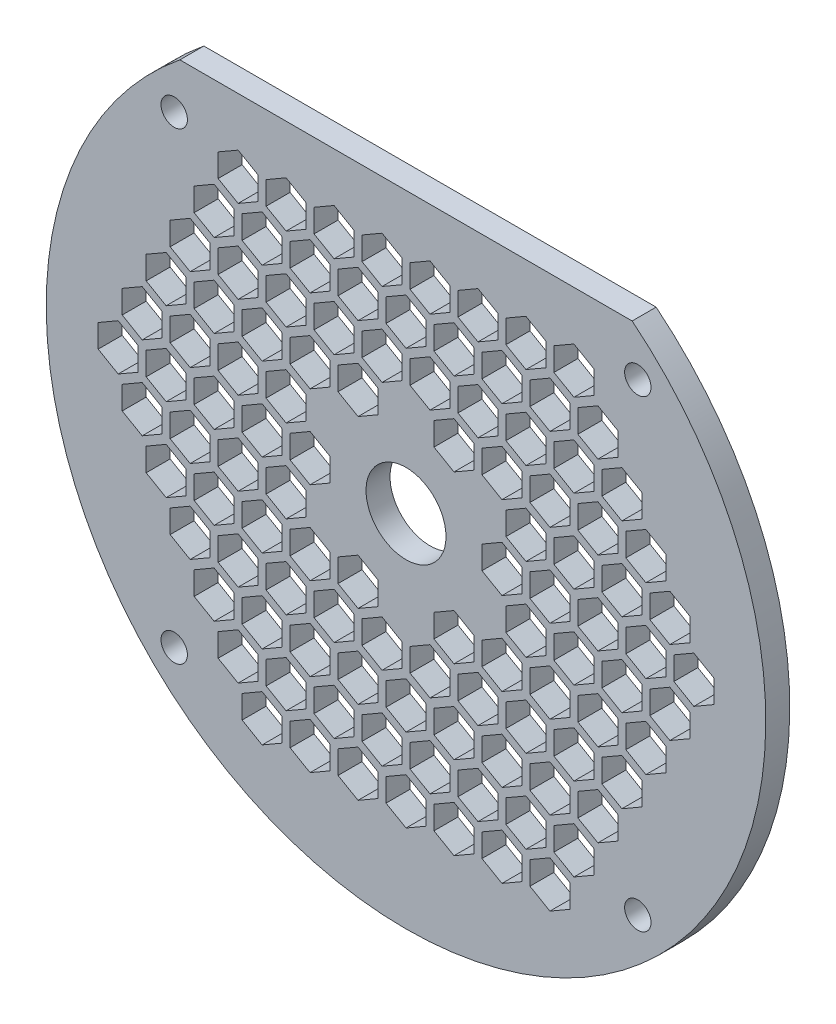
SolidWorks part; units mm, degrees
ref_plane "前视基准面" through (0, 0, 0) normal (0, 0, 1) x (1, 0, 0)
ref_plane "上视基准面" through (0, 0, 0) normal (0, 1, 0) x (1, 0, 0)
ref_plane "右视基准面" through (0, 0, 0) normal (1, 0, 0) x (0, 0, -1)
sketch "草图1" plane through (0, 0, 0) normal (0, 0, 1) x (1, 0, 0)
  circle A0 centre (0, 0) radius 90
extrude "凸台-拉伸1" add sketch "草图1" along normal blind 6
sketch "草图3" plane through (0, 0, 0) normal (0, 0, 1) x (1, 0, 0)
  circle A0 centre (0, 0) radius 10
extrude "切除-拉伸2" cut sketch "草图3" along normal through all
sketch "草图4" plane through (0, 0, 0) normal (0, 0, 1) x (1, 0, 0)
  circle A0 centre (57.9828, 57.9828) radius 3.3
  circle A1 centre (-57.9828, 57.9828) radius 3.3
  circle A2 centre (-57.9828, -57.9828) radius 3.3
  circle A3 centre (57.9828, -57.9828) radius 3.3
extrude "切除-拉伸3" cut sketch "草图4" along normal through all
sketch "草图5" plane through (0, 0, 0) normal (0, 0, 1) x (1, 0, 0)
  line L0 (-110, 70) -> (110, 70)
  line L1 (110, 70) -> (110, 110)
  line L2 (110, 110) -> (-110, 110)
  line L3 (-110, 110) -> (-110, 70)
extrude "切除-拉伸4" cut sketch "草图5" along normal through all
sketch "草图6" plane through (0, 0, 0) normal (0, 0, 1) x (1, 0, 0)
  line L0 (0, -56.5785) -> (5, -59.4653)
  line L1 (5, -59.4653) -> (5, -65.2388)
  line L2 (5, -65.2388) -> (0, -68.1255)
  line L3 (0, -68.1255) -> (-5, -65.2388)
  line L4 (-5, -65.2388) -> (-5, -59.4653)
  line L5 (-5, -59.4653) -> (0, -56.5785)
  line L6 (12, -56.5785) -> (17, -59.4653)
  line L7 (17, -59.4653) -> (17, -65.2388)
  line L8 (17, -65.2388) -> (12, -68.1255)
  line L9 (12, -68.1255) -> (7, -65.2388)
  line L10 (7, -65.2388) -> (7, -59.4653)
  line L11 (7, -59.4653) -> (12, -56.5785)
  line L12 (-12, -56.5785) -> (-7, -59.4653)
  line L13 (-7, -59.4653) -> (-7, -65.2388)
  line L14 (-7, -65.2388) -> (-12, -68.1255)
  line L15 (-12, -68.1255) -> (-17, -65.2388)
  line L16 (-17, -65.2388) -> (-17, -59.4653)
  line L17 (-17, -59.4653) -> (-12, -56.5785)
  line L18 (24, -56.5785) -> (29, -59.4653)
  line L19 (29, -59.4653) -> (29, -65.2388)
  line L20 (29, -65.2388) -> (24, -68.1255)
  line L21 (24, -68.1255) -> (19, -65.2388)
  line L22 (19, -65.2388) -> (19, -59.4653)
  line L23 (19, -59.4653) -> (24, -56.5785)
  line L24 (-24, -56.5785) -> (-19, -59.4653)
  line L25 (-19, -59.4653) -> (-19, -65.2388)
  line L26 (-19, -65.2388) -> (-24, -68.1255)
  line L27 (-24, -68.1255) -> (-29, -65.2388)
  line L28 (-29, -65.2388) -> (-29, -59.4653)
  line L29 (-29, -59.4653) -> (-24, -56.5785)
  line L30 (36, -56.5785) -> (41, -59.4653)
  line L31 (41, -59.4653) -> (41, -65.2388)
  line L32 (41, -65.2388) -> (36, -68.1255)
  line L33 (36, -68.1255) -> (31, -65.2388)
  line L34 (31, -65.2388) -> (31, -59.4653)
  line L35 (31, -59.4653) -> (36, -56.5785)
  line L36 (-36, -56.5785) -> (-31, -59.4653)
  line L37 (-31, -59.4653) -> (-31, -65.2388)
  line L38 (-31, -65.2388) -> (-36, -68.1255)
  line L39 (-36, -68.1255) -> (-41, -65.2388)
  line L40 (-41, -65.2388) -> (-41, -59.4653)
  line L41 (-41, -59.4653) -> (-36, -56.5785)
  line L42 (6, -46.1865) -> (11, -49.0733)
  line L43 (11, -49.0733) -> (11, -54.8468)
  line L44 (11, -54.8468) -> (6, -57.7335)
  line L45 (6, -57.7335) -> (1, -54.8468)
  line L46 (1, -54.8468) -> (1, -49.0733)
  line L47 (1, -49.0733) -> (6, -46.1865)
  line L48 (-6, -46.1865) -> (-1, -49.0733)
  line L49 (-1, -49.0733) -> (-1, -54.8468)
  line L50 (-1, -54.8468) -> (-6, -57.7335)
  line L51 (-6, -57.7335) -> (-11, -54.8468)
  line L52 (-11, -54.8468) -> (-11, -49.0733)
  line L53 (-11, -49.0733) -> (-6, -46.1865)
  line L54 (18, -46.1865) -> (23, -49.0733)
  line L55 (23, -49.0733) -> (23, -54.8468)
  line L56 (23, -54.8468) -> (18, -57.7335)
  line L57 (18, -57.7335) -> (13, -54.8468)
  line L58 (13, -54.8468) -> (13, -49.0733)
  line L59 (13, -49.0733) -> (18, -46.1865)
  line L60 (-18, -46.1865) -> (-13, -49.0733)
  line L61 (-13, -49.0733) -> (-13, -54.8468)
  line L62 (-13, -54.8468) -> (-18, -57.7335)
  line L63 (-18, -57.7335) -> (-23, -54.8468)
  line L64 (-23, -54.8468) -> (-23, -49.0733)
  line L65 (-23, -49.0733) -> (-18, -46.1865)
  line L66 (30, -46.1865) -> (35, -49.0733)
  line L67 (35, -49.0733) -> (35, -54.8468)
  line L68 (35, -54.8468) -> (30, -57.7335)
  line L69 (30, -57.7335) -> (25, -54.8468)
  line L70 (25, -54.8468) -> (25, -49.0733)
  line L71 (25, -49.0733) -> (30, -46.1865)
  line L72 (-30, -46.1865) -> (-25, -49.0733)
  line L73 (-25, -49.0733) -> (-25, -54.8468)
  line L74 (-25, -54.8468) -> (-30, -57.7335)
  line L75 (-30, -57.7335) -> (-35, -54.8468)
  line L76 (-35, -54.8468) -> (-35, -49.0733)
  line L77 (-35, -49.0733) -> (-30, -46.1865)
  line L78 (42, -46.1865) -> (47, -49.0733)
  line L79 (47, -49.0733) -> (47, -54.8468)
  line L80 (47, -54.8468) -> (42, -57.7335)
  line L81 (42, -57.7335) -> (37, -54.8468)
  line L82 (37, -54.8468) -> (37, -49.0733)
  line L83 (37, -49.0733) -> (42, -46.1865)
  line L84 (-42, -46.1865) -> (-37, -49.0733)
  line L85 (-37, -49.0733) -> (-37, -54.8468)
  line L86 (-37, -54.8468) -> (-42, -57.7335)
  line L87 (-42, -57.7335) -> (-47, -54.8468)
  line L88 (-47, -54.8468) -> (-47, -49.0733)
  line L89 (-47, -49.0733) -> (-42, -46.1865)
  line L90 (0, -35.7945) -> (5, -38.6813)
  line L91 (5, -38.6813) -> (5, -44.4548)
  line L92 (5, -44.4548) -> (0, -47.3415)
  line L93 (0, -47.3415) -> (-5, -44.4548)
  line L94 (-5, -44.4548) -> (-5, -38.6813)
  line L95 (-5, -38.6813) -> (0, -35.7945)
  line L96 (12, -35.7945) -> (17, -38.6813)
  line L97 (17, -38.6813) -> (17, -44.4548)
  line L98 (17, -44.4548) -> (12, -47.3415)
  line L99 (12, -47.3415) -> (7, -44.4548)
  line L100 (7, -44.4548) -> (7, -38.6813)
  line L101 (7, -38.6813) -> (12, -35.7945)
  line L102 (-12, -35.7945) -> (-7, -38.6813)
  line L103 (-7, -38.6813) -> (-7, -44.4548)
  line L104 (-7, -44.4548) -> (-12, -47.3415)
  line L105 (-12, -47.3415) -> (-17, -44.4548)
  line L106 (-17, -44.4548) -> (-17, -38.6813)
  line L107 (-17, -38.6813) -> (-12, -35.7945)
  line L108 (24, -35.7945) -> (29, -38.6813)
  line L109 (29, -38.6813) -> (29, -44.4548)
  line L110 (29, -44.4548) -> (24, -47.3415)
  line L111 (24, -47.3415) -> (19, -44.4548)
  line L112 (19, -44.4548) -> (19, -38.6813)
  line L113 (19, -38.6813) -> (24, -35.7945)
  line L114 (-24, -35.7945) -> (-19, -38.6813)
  line L115 (-19, -38.6813) -> (-19, -44.4548)
  line L116 (-19, -44.4548) -> (-24, -47.3415)
  line L117 (-24, -47.3415) -> (-29, -44.4548)
  line L118 (-29, -44.4548) -> (-29, -38.6813)
  line L119 (-29, -38.6813) -> (-24, -35.7945)
  line L120 (36, -35.7945) -> (41, -38.6813)
  line L121 (41, -38.6813) -> (41, -44.4548)
  line L122 (41, -44.4548) -> (36, -47.3415)
  line L123 (36, -47.3415) -> (31, -44.4548)
  line L124 (31, -44.4548) -> (31, -38.6813)
  line L125 (31, -38.6813) -> (36, -35.7945)
  line L126 (-36, -35.7945) -> (-31, -38.6813)
  line L127 (-31, -38.6813) -> (-31, -44.4548)
  line L128 (-31, -44.4548) -> (-36, -47.3415)
  line L129 (-36, -47.3415) -> (-41, -44.4548)
  line L130 (-41, -44.4548) -> (-41, -38.6813)
  line L131 (-41, -38.6813) -> (-36, -35.7945)
  line L132 (48, -35.7945) -> (53, -38.6813)
  line L133 (53, -38.6813) -> (53, -44.4548)
  line L134 (53, -44.4548) -> (48, -47.3415)
  line L135 (48, -47.3415) -> (43, -44.4548)
  line L136 (43, -44.4548) -> (43, -38.6813)
  line L137 (43, -38.6813) -> (48, -35.7945)
  line L138 (-48, -35.7945) -> (-43, -38.6813)
  line L139 (-43, -38.6813) -> (-43, -44.4548)
  line L140 (-43, -44.4548) -> (-48, -47.3415)
  line L141 (-48, -47.3415) -> (-53, -44.4548)
  line L142 (-53, -44.4548) -> (-53, -38.6813)
  line L143 (-53, -38.6813) -> (-48, -35.7945)
extrude "切除-拉伸5" cut sketch "草图6" along normal through all
sketch "草图8" plane through (0, 0, 0) normal (0, 0, 1) x (1, 0, 0)
  line L0 (6, -25.4025) -> (11, -28.2893)
  line L1 (11, -28.2893) -> (11, -34.0628)
  line L2 (11, -34.0628) -> (6, -36.9495)
  line L3 (6, -36.9495) -> (1, -34.0628)
  line L4 (1, -34.0628) -> (1, -28.2893)
  line L5 (1, -28.2893) -> (6, -25.4025)
  line L6 (-6, -25.4025) -> (-1, -28.2893)
  line L7 (-1, -28.2893) -> (-1, -34.0628)
  line L8 (-1, -34.0628) -> (-6, -36.9495)
  line L9 (-6, -36.9495) -> (-11, -34.0628)
  line L10 (-11, -34.0628) -> (-11, -28.2893)
  line L11 (-11, -28.2893) -> (-6, -25.4025)
  line L12 (18, -25.4025) -> (23, -28.2893)
  line L13 (23, -28.2893) -> (23, -34.0628)
  line L14 (23, -34.0628) -> (18, -36.9495)
  line L15 (18, -36.9495) -> (13, -34.0628)
  line L16 (13, -34.0628) -> (13, -28.2893)
  line L17 (13, -28.2893) -> (18, -25.4025)
  line L18 (-18, -25.4025) -> (-13, -28.2893)
  line L19 (-13, -28.2893) -> (-13, -34.0628)
  line L20 (-13, -34.0628) -> (-18, -36.9495)
  line L21 (-18, -36.9495) -> (-23, -34.0628)
  line L22 (-23, -34.0628) -> (-23, -28.2893)
  line L23 (-23, -28.2893) -> (-18, -25.4025)
  line L24 (30, -25.4025) -> (35, -28.2893)
  line L25 (35, -28.2893) -> (35, -34.0628)
  line L26 (35, -34.0628) -> (30, -36.9495)
  line L27 (30, -36.9495) -> (25, -34.0628)
  line L28 (25, -34.0628) -> (25, -28.2893)
  line L29 (25, -28.2893) -> (30, -25.4025)
  line L30 (-30, -25.4025) -> (-25, -28.2893)
  line L31 (-25, -28.2893) -> (-25, -34.0628)
  line L32 (-25, -34.0628) -> (-30, -36.9495)
  line L33 (-30, -36.9495) -> (-35, -34.0628)
  line L34 (-35, -34.0628) -> (-35, -28.2893)
  line L35 (-35, -28.2893) -> (-30, -25.4025)
  line L36 (42, -25.4025) -> (47, -28.2893)
  line L37 (47, -28.2893) -> (47, -34.0628)
  line L38 (47, -34.0628) -> (42, -36.9495)
  line L39 (42, -36.9495) -> (37, -34.0628)
  line L40 (37, -34.0628) -> (37, -28.2893)
  line L41 (37, -28.2893) -> (42, -25.4025)
  line L42 (-42, -25.4025) -> (-37, -28.2893)
  line L43 (-37, -28.2893) -> (-37, -34.0628)
  line L44 (-37, -34.0628) -> (-42, -36.9495)
  line L45 (-42, -36.9495) -> (-47, -34.0628)
  line L46 (-47, -34.0628) -> (-47, -28.2893)
  line L47 (-47, -28.2893) -> (-42, -25.4025)
  line L48 (54, -25.4025) -> (59, -28.2893)
  line L49 (59, -28.2893) -> (59, -34.0628)
  line L50 (59, -34.0628) -> (54, -36.9495)
  line L51 (54, -36.9495) -> (49, -34.0628)
  line L52 (49, -34.0628) -> (49, -28.2893)
  line L53 (49, -28.2893) -> (54, -25.4025)
  line L54 (-54, -25.4025) -> (-49, -28.2893)
  line L55 (-49, -28.2893) -> (-49, -34.0628)
  line L56 (-49, -34.0628) -> (-54, -36.9495)
  line L57 (-54, -36.9495) -> (-59, -34.0628)
  line L58 (-59, -34.0628) -> (-59, -28.2893)
  line L59 (-59, -28.2893) -> (-54, -25.4025)
  line L60 (12, -15.0105) -> (17, -17.8973)
  line L61 (17, -17.8973) -> (17, -23.6708)
  line L62 (17, -23.6708) -> (12, -26.5575)
  line L63 (12, -26.5575) -> (7, -23.6708)
  line L64 (7, -23.6708) -> (7, -17.8973)
  line L65 (7, -17.8973) -> (12, -15.0105)
  line L66 (-12, -15.0105) -> (-7, -17.8973)
  line L67 (-7, -17.8973) -> (-7, -23.6708)
  line L68 (-7, -23.6708) -> (-12, -26.5575)
  line L69 (-12, -26.5575) -> (-17, -23.6708)
  line L70 (-17, -23.6708) -> (-17, -17.8973)
  line L71 (-17, -17.8973) -> (-12, -15.0105)
  line L72 (24, -15.0105) -> (29, -17.8973)
  line L73 (29, -17.8973) -> (29, -23.6708)
  line L74 (29, -23.6708) -> (24, -26.5575)
  line L75 (24, -26.5575) -> (19, -23.6708)
  line L76 (19, -23.6708) -> (19, -17.8973)
  line L77 (19, -17.8973) -> (24, -15.0105)
  line L78 (-24, -15.0105) -> (-19, -17.8973)
  line L79 (-19, -17.8973) -> (-19, -23.6708)
  line L80 (-19, -23.6708) -> (-24, -26.5575)
  line L81 (-24, -26.5575) -> (-29, -23.6708)
  line L82 (-29, -23.6708) -> (-29, -17.8973)
  line L83 (-29, -17.8973) -> (-24, -15.0105)
  line L84 (36, -15.0105) -> (41, -17.8973)
  line L85 (41, -17.8973) -> (41, -23.6708)
  line L86 (41, -23.6708) -> (36, -26.5575)
  line L87 (36, -26.5575) -> (31, -23.6708)
  line L88 (31, -23.6708) -> (31, -17.8973)
  line L89 (31, -17.8973) -> (36, -15.0105)
  line L90 (-36, -15.0105) -> (-31, -17.8973)
  line L91 (-31, -17.8973) -> (-31, -23.6708)
  line L92 (-31, -23.6708) -> (-36, -26.5575)
  line L93 (-36, -26.5575) -> (-41, -23.6708)
  line L94 (-41, -23.6708) -> (-41, -17.8973)
  line L95 (-41, -17.8973) -> (-36, -15.0105)
  line L96 (48, -15.0105) -> (53, -17.8973)
  line L97 (53, -17.8973) -> (53, -23.6708)
  line L98 (53, -23.6708) -> (48, -26.5575)
  line L99 (48, -26.5575) -> (43, -23.6708)
  line L100 (43, -23.6708) -> (43, -17.8973)
  line L101 (43, -17.8973) -> (48, -15.0105)
  line L102 (-48, -15.0105) -> (-43, -17.8973)
  line L103 (-43, -17.8973) -> (-43, -23.6708)
  line L104 (-43, -23.6708) -> (-48, -26.5575)
  line L105 (-48, -26.5575) -> (-53, -23.6708)
  line L106 (-53, -23.6708) -> (-53, -17.8973)
  line L107 (-53, -17.8973) -> (-48, -15.0105)
  line L108 (60, -15.0105) -> (65, -17.8973)
  line L109 (65, -17.8973) -> (65, -23.6708)
  line L110 (65, -23.6708) -> (60, -26.5575)
  line L111 (60, -26.5575) -> (55, -23.6708)
  line L112 (55, -23.6708) -> (55, -17.8973)
  line L113 (55, -17.8973) -> (60, -15.0105)
  line L114 (-60, -15.0105) -> (-55, -17.8973)
  line L115 (-55, -17.8973) -> (-55, -23.6708)
  line L116 (-55, -23.6708) -> (-60, -26.5575)
  line L117 (-60, -26.5575) -> (-65, -23.6708)
  line L118 (-65, -23.6708) -> (-65, -17.8973)
  line L119 (-65, -17.8973) -> (-60, -15.0105)
  line L120 (30, -4.6185) -> (35, -7.5053)
  line L121 (35, -7.5053) -> (35, -13.2788)
  line L122 (35, -13.2788) -> (30, -16.1655)
  line L123 (30, -16.1655) -> (25, -13.2788)
  line L124 (25, -13.2788) -> (25, -7.5053)
  line L125 (25, -7.5053) -> (30, -4.6185)
  line L126 (-30, -4.6185) -> (-25, -7.5053)
  line L127 (-25, -7.5053) -> (-25, -13.2788)
  line L128 (-25, -13.2788) -> (-30, -16.1655)
  line L129 (-30, -16.1655) -> (-35, -13.2788)
  line L130 (-35, -13.2788) -> (-35, -7.5053)
  line L131 (-35, -7.5053) -> (-30, -4.6185)
  line L132 (42, -4.6185) -> (47, -7.5053)
  line L133 (47, -7.5053) -> (47, -13.2788)
  line L134 (47, -13.2788) -> (42, -16.1655)
  line L135 (42, -16.1655) -> (37, -13.2788)
  line L136 (37, -13.2788) -> (37, -7.5053)
  line L137 (37, -7.5053) -> (42, -4.6185)
  line L138 (-42, -4.6185) -> (-37, -7.5053)
  line L139 (-37, -7.5053) -> (-37, -13.2788)
  line L140 (-37, -13.2788) -> (-42, -16.1655)
  line L141 (-42, -16.1655) -> (-47, -13.2788)
  line L142 (-47, -13.2788) -> (-47, -7.5053)
  line L143 (-47, -7.5053) -> (-42, -4.6185)
  line L144 (54, -4.6185) -> (59, -7.5053)
  line L145 (59, -7.5053) -> (59, -13.2788)
  line L146 (59, -13.2788) -> (54, -16.1655)
  line L147 (54, -16.1655) -> (49, -13.2788)
  line L148 (49, -13.2788) -> (49, -7.5053)
  line L149 (49, -7.5053) -> (54, -4.6185)
  line L150 (-54, -4.6185) -> (-49, -7.5053)
  line L151 (-49, -7.5053) -> (-49, -13.2788)
  line L152 (-49, -13.2788) -> (-54, -16.1655)
  line L153 (-54, -16.1655) -> (-59, -13.2788)
  line L154 (-59, -13.2788) -> (-59, -7.5053)
  line L155 (-59, -7.5053) -> (-54, -4.6185)
  line L156 (66, -4.6185) -> (71, -7.5053)
  line L157 (71, -7.5053) -> (71, -13.2788)
  line L158 (71, -13.2788) -> (66, -16.1655)
  line L159 (66, -16.1655) -> (61, -13.2788)
  line L160 (61, -13.2788) -> (61, -7.5053)
  line L161 (61, -7.5053) -> (66, -4.6185)
  line L162 (-66, -4.6185) -> (-61, -7.5053)
  line L163 (-61, -7.5053) -> (-61, -13.2788)
  line L164 (-61, -13.2788) -> (-66, -16.1655)
  line L165 (-66, -16.1655) -> (-71, -13.2788)
  line L166 (-71, -13.2788) -> (-71, -7.5053)
  line L167 (-71, -7.5053) -> (-66, -4.6185)
extrude "切除-拉伸7" cut sketch "草图8" along normal through all
sketch "草图9" plane through (0, 0, 0) normal (0, 0, 1) x (1, 0, 0)
  line L0 (24, 5.7735) -> (29, 2.8868)
  line L1 (29, 2.8868) -> (29, -2.8868)
  line L2 (29, -2.8868) -> (24, -5.7735)
  line L3 (24, -5.7735) -> (19, -2.8868)
  line L4 (19, -2.8868) -> (19, 2.8868)
  line L5 (19, 2.8868) -> (24, 5.7735)
  line L6 (-24, 5.7735) -> (-19, 2.8868)
  line L7 (-19, 2.8868) -> (-19, -2.8868)
  line L8 (-19, -2.8868) -> (-24, -5.7735)
  line L9 (-24, -5.7735) -> (-29, -2.8868)
  line L10 (-29, -2.8868) -> (-29, 2.8868)
  line L11 (-29, 2.8868) -> (-24, 5.7735)
  line L12 (36, 5.7735) -> (41, 2.8868)
  line L13 (41, 2.8868) -> (41, -2.8868)
  line L14 (41, -2.8868) -> (36, -5.7735)
  line L15 (36, -5.7735) -> (31, -2.8868)
  line L16 (31, -2.8868) -> (31, 2.8868)
  line L17 (31, 2.8868) -> (36, 5.7735)
  line L18 (-36, 5.7735) -> (-31, 2.8868)
  line L19 (-31, 2.8868) -> (-31, -2.8868)
  line L20 (-31, -2.8868) -> (-36, -5.7735)
  line L21 (-36, -5.7735) -> (-41, -2.8868)
  line L22 (-41, -2.8868) -> (-41, 2.8868)
  line L23 (-41, 2.8868) -> (-36, 5.7735)
  line L24 (48, 5.7735) -> (53, 2.8868)
  line L25 (53, 2.8868) -> (53, -2.8868)
  line L26 (53, -2.8868) -> (48, -5.7735)
  line L27 (48, -5.7735) -> (43, -2.8868)
  line L28 (43, -2.8868) -> (43, 2.8868)
  line L29 (43, 2.8868) -> (48, 5.7735)
  line L30 (-48, 5.7735) -> (-43, 2.8868)
  line L31 (-43, 2.8868) -> (-43, -2.8868)
  line L32 (-43, -2.8868) -> (-48, -5.7735)
  line L33 (-48, -5.7735) -> (-53, -2.8868)
  line L34 (-53, -2.8868) -> (-53, 2.8868)
  line L35 (-53, 2.8868) -> (-48, 5.7735)
  line L36 (60, 5.7735) -> (65, 2.8868)
  line L37 (65, 2.8868) -> (65, -2.8868)
  line L38 (65, -2.8868) -> (60, -5.7735)
  line L39 (60, -5.7735) -> (55, -2.8868)
  line L40 (55, -2.8868) -> (55, 2.8868)
  line L41 (55, 2.8868) -> (60, 5.7735)
  line L42 (-60, 5.7735) -> (-55, 2.8868)
  line L43 (-55, 2.8868) -> (-55, -2.8868)
  line L44 (-55, -2.8868) -> (-60, -5.7735)
  line L45 (-60, -5.7735) -> (-65, -2.8868)
  line L46 (-65, -2.8868) -> (-65, 2.8868)
  line L47 (-65, 2.8868) -> (-60, 5.7735)
  line L48 (72, 5.7735) -> (77, 2.8868)
  line L49 (77, 2.8868) -> (77, -2.8868)
  line L50 (77, -2.8868) -> (72, -5.7735)
  line L51 (72, -5.7735) -> (67, -2.8868)
  line L52 (67, -2.8868) -> (67, 2.8868)
  line L53 (67, 2.8868) -> (72, 5.7735)
  line L54 (-72, 5.7735) -> (-67, 2.8868)
  line L55 (-67, 2.8868) -> (-67, -2.8868)
  line L56 (-67, -2.8868) -> (-72, -5.7735)
  line L57 (-72, -5.7735) -> (-77, -2.8868)
  line L58 (-77, -2.8868) -> (-77, 2.8868)
  line L59 (-77, 2.8868) -> (-72, 5.7735)
  line L60 (30, 16.1655) -> (35, 13.2788)
  line L61 (35, 13.2788) -> (35, 7.5053)
  line L62 (35, 7.5053) -> (30, 4.6185)
  line L63 (30, 4.6185) -> (25, 7.5053)
  line L64 (25, 7.5053) -> (25, 13.2788)
  line L65 (25, 13.2788) -> (30, 16.1655)
  line L66 (-30, 16.1655) -> (-25, 13.2788)
  line L67 (-25, 13.2788) -> (-25, 7.5053)
  line L68 (-25, 7.5053) -> (-30, 4.6185)
  line L69 (-30, 4.6185) -> (-35, 7.5053)
  line L70 (-35, 7.5053) -> (-35, 13.2788)
  line L71 (-35, 13.2788) -> (-30, 16.1655)
  line L72 (42, 16.1655) -> (47, 13.2788)
  line L73 (47, 13.2788) -> (47, 7.5053)
  line L74 (47, 7.5053) -> (42, 4.6185)
  line L75 (42, 4.6185) -> (37, 7.5053)
  line L76 (37, 7.5053) -> (37, 13.2788)
  line L77 (37, 13.2788) -> (42, 16.1655)
  line L78 (-42, 16.1655) -> (-37, 13.2788)
  line L79 (-37, 13.2788) -> (-37, 7.5053)
  line L80 (-37, 7.5053) -> (-42, 4.6185)
  line L81 (-42, 4.6185) -> (-47, 7.5053)
  line L82 (-47, 7.5053) -> (-47, 13.2788)
  line L83 (-47, 13.2788) -> (-42, 16.1655)
  line L84 (54, 16.1655) -> (59, 13.2788)
  line L85 (59, 13.2788) -> (59, 7.5053)
  line L86 (59, 7.5053) -> (54, 4.6185)
  line L87 (54, 4.6185) -> (49, 7.5053)
  line L88 (49, 7.5053) -> (49, 13.2788)
  line L89 (49, 13.2788) -> (54, 16.1655)
  line L90 (-54, 16.1655) -> (-49, 13.2788)
  line L91 (-49, 13.2788) -> (-49, 7.5053)
  line L92 (-49, 7.5053) -> (-54, 4.6185)
  line L93 (-54, 4.6185) -> (-59, 7.5053)
  line L94 (-59, 7.5053) -> (-59, 13.2788)
  line L95 (-59, 13.2788) -> (-54, 16.1655)
  line L96 (66, 16.1655) -> (71, 13.2788)
  line L97 (71, 13.2788) -> (71, 7.5053)
  line L98 (71, 7.5053) -> (66, 4.6185)
  line L99 (66, 4.6185) -> (61, 7.5053)
  line L100 (61, 7.5053) -> (61, 13.2788)
  line L101 (61, 13.2788) -> (66, 16.1655)
  line L102 (-66, 16.1655) -> (-61, 13.2788)
  line L103 (-61, 13.2788) -> (-61, 7.5053)
  line L104 (-61, 7.5053) -> (-66, 4.6185)
  line L105 (-66, 4.6185) -> (-71, 7.5053)
  line L106 (-71, 7.5053) -> (-71, 13.2788)
  line L107 (-71, 13.2788) -> (-66, 16.1655)
  line L108 (12, 26.5575) -> (17, 23.6708)
  line L109 (17, 23.6708) -> (17, 17.8973)
  line L110 (17, 17.8973) -> (12, 15.0105)
  line L111 (12, 15.0105) -> (7, 17.8973)
  line L112 (7, 17.8973) -> (7, 23.6708)
  line L113 (7, 23.6708) -> (12, 26.5575)
  line L114 (-12, 26.5575) -> (-7, 23.6708)
  line L115 (-7, 23.6708) -> (-7, 17.8973)
  line L116 (-7, 17.8973) -> (-12, 15.0105)
  line L117 (-12, 15.0105) -> (-17, 17.8973)
  line L118 (-17, 17.8973) -> (-17, 23.6708)
  line L119 (-17, 23.6708) -> (-12, 26.5575)
  line L120 (24, 26.5575) -> (29, 23.6708)
  line L121 (29, 23.6708) -> (29, 17.8973)
  line L122 (29, 17.8973) -> (24, 15.0105)
  line L123 (24, 15.0105) -> (19, 17.8973)
  line L124 (19, 17.8973) -> (19, 23.6708)
  line L125 (19, 23.6708) -> (24, 26.5575)
  line L126 (-24, 26.5575) -> (-19, 23.6708)
  line L127 (-19, 23.6708) -> (-19, 17.8973)
  line L128 (-19, 17.8973) -> (-24, 15.0105)
  line L129 (-24, 15.0105) -> (-29, 17.8973)
  line L130 (-29, 17.8973) -> (-29, 23.6708)
  line L131 (-29, 23.6708) -> (-24, 26.5575)
  line L132 (36, 26.5575) -> (41, 23.6708)
  line L133 (41, 23.6708) -> (41, 17.8973)
  line L134 (41, 17.8973) -> (36, 15.0105)
  line L135 (36, 15.0105) -> (31, 17.8973)
  line L136 (31, 17.8973) -> (31, 23.6708)
  line L137 (31, 23.6708) -> (36, 26.5575)
  line L138 (-36, 26.5575) -> (-31, 23.6708)
  line L139 (-31, 23.6708) -> (-31, 17.8973)
  line L140 (-31, 17.8973) -> (-36, 15.0105)
  line L141 (-36, 15.0105) -> (-41, 17.8973)
  line L142 (-41, 17.8973) -> (-41, 23.6708)
  line L143 (-41, 23.6708) -> (-36, 26.5575)
  line L144 (48, 26.5575) -> (53, 23.6708)
  line L145 (53, 23.6708) -> (53, 17.8973)
  line L146 (53, 17.8973) -> (48, 15.0105)
  line L147 (48, 15.0105) -> (43, 17.8973)
  line L148 (43, 17.8973) -> (43, 23.6708)
  line L149 (43, 23.6708) -> (48, 26.5575)
  line L150 (-48, 26.5575) -> (-43, 23.6708)
  line L151 (-43, 23.6708) -> (-43, 17.8973)
  line L152 (-43, 17.8973) -> (-48, 15.0105)
  line L153 (-48, 15.0105) -> (-53, 17.8973)
  line L154 (-53, 17.8973) -> (-53, 23.6708)
  line L155 (-53, 23.6708) -> (-48, 26.5575)
  line L156 (60, 26.5575) -> (65, 23.6708)
  line L157 (65, 23.6708) -> (65, 17.8973)
  line L158 (65, 17.8973) -> (60, 15.0105)
  line L159 (60, 15.0105) -> (55, 17.8973)
  line L160 (55, 17.8973) -> (55, 23.6708)
  line L161 (55, 23.6708) -> (60, 26.5575)
  line L162 (-60, 26.5575) -> (-55, 23.6708)
  line L163 (-55, 23.6708) -> (-55, 17.8973)
  line L164 (-55, 17.8973) -> (-60, 15.0105)
  line L165 (-60, 15.0105) -> (-65, 17.8973)
  line L166 (-65, 17.8973) -> (-65, 23.6708)
  line L167 (-65, 23.6708) -> (-60, 26.5575)
extrude "切除-拉伸8" cut sketch "草图9" along normal through all
sketch "草图10" plane through (0, 0, 0) normal (0, 0, 1) x (1, 0, 0)
  line L0 (6, 36.9495) -> (11, 34.0628)
  line L1 (11, 34.0628) -> (11, 28.2893)
  line L2 (11, 28.2893) -> (6, 25.4025)
  line L3 (6, 25.4025) -> (1, 28.2893)
  line L4 (1, 28.2893) -> (1, 34.0628)
  line L5 (1, 34.0628) -> (6, 36.9495)
  line L6 (-6, 36.9495) -> (-1, 34.0628)
  line L7 (-1, 34.0628) -> (-1, 28.2893)
  line L8 (-1, 28.2893) -> (-6, 25.4025)
  line L9 (-6, 25.4025) -> (-11, 28.2893)
  line L10 (-11, 28.2893) -> (-11, 34.0628)
  line L11 (-11, 34.0628) -> (-6, 36.9495)
  line L12 (18, 36.9495) -> (23, 34.0628)
  line L13 (23, 34.0628) -> (23, 28.2893)
  line L14 (23, 28.2893) -> (18, 25.4025)
  line L15 (18, 25.4025) -> (13, 28.2893)
  line L16 (13, 28.2893) -> (13, 34.0628)
  line L17 (13, 34.0628) -> (18, 36.9495)
  line L18 (-18, 36.9495) -> (-13, 34.0628)
  line L19 (-13, 34.0628) -> (-13, 28.2893)
  line L20 (-13, 28.2893) -> (-18, 25.4025)
  line L21 (-18, 25.4025) -> (-23, 28.2893)
  line L22 (-23, 28.2893) -> (-23, 34.0628)
  line L23 (-23, 34.0628) -> (-18, 36.9495)
  line L24 (30, 36.9495) -> (35, 34.0628)
  line L25 (35, 34.0628) -> (35, 28.2893)
  line L26 (35, 28.2893) -> (30, 25.4025)
  line L27 (30, 25.4025) -> (25, 28.2893)
  line L28 (25, 28.2893) -> (25, 34.0628)
  line L29 (25, 34.0628) -> (30, 36.9495)
  line L30 (-30, 36.9495) -> (-25, 34.0628)
  line L31 (-25, 34.0628) -> (-25, 28.2893)
  line L32 (-25, 28.2893) -> (-30, 25.4025)
  line L33 (-30, 25.4025) -> (-35, 28.2893)
  line L34 (-35, 28.2893) -> (-35, 34.0628)
  line L35 (-35, 34.0628) -> (-30, 36.9495)
  line L36 (42, 36.9495) -> (47, 34.0628)
  line L37 (47, 34.0628) -> (47, 28.2893)
  line L38 (47, 28.2893) -> (42, 25.4025)
  line L39 (42, 25.4025) -> (37, 28.2893)
  line L40 (37, 28.2893) -> (37, 34.0628)
  line L41 (37, 34.0628) -> (42, 36.9495)
  line L42 (-42, 36.9495) -> (-37, 34.0628)
  line L43 (-37, 34.0628) -> (-37, 28.2893)
  line L44 (-37, 28.2893) -> (-42, 25.4025)
  line L45 (-42, 25.4025) -> (-47, 28.2893)
  line L46 (-47, 28.2893) -> (-47, 34.0628)
  line L47 (-47, 34.0628) -> (-42, 36.9495)
  line L48 (54, 36.9495) -> (59, 34.0628)
  line L49 (59, 34.0628) -> (59, 28.2893)
  line L50 (59, 28.2893) -> (54, 25.4025)
  line L51 (54, 25.4025) -> (49, 28.2893)
  line L52 (49, 28.2893) -> (49, 34.0628)
  line L53 (49, 34.0628) -> (54, 36.9495)
  line L54 (-54, 36.9495) -> (-49, 34.0628)
  line L55 (-49, 34.0628) -> (-49, 28.2893)
  line L56 (-49, 28.2893) -> (-54, 25.4025)
  line L57 (-54, 25.4025) -> (-59, 28.2893)
  line L58 (-59, 28.2893) -> (-59, 34.0628)
  line L59 (-59, 34.0628) -> (-54, 36.9495)
  line L60 (0, 47.3415) -> (5, 44.4548)
  line L61 (5, 44.4548) -> (5, 38.6813)
  line L62 (5, 38.6813) -> (0, 35.7945)
  line L63 (0, 35.7945) -> (-5, 38.6813)
  line L64 (-5, 38.6813) -> (-5, 44.4548)
  line L65 (-5, 44.4548) -> (0, 47.3415)
  line L66 (12, 47.3415) -> (17, 44.4548)
  line L67 (17, 44.4548) -> (17, 38.6813)
  line L68 (17, 38.6813) -> (12, 35.7945)
  line L69 (12, 35.7945) -> (7, 38.6813)
  line L70 (7, 38.6813) -> (7, 44.4548)
  line L71 (7, 44.4548) -> (12, 47.3415)
  line L72 (-12, 47.3415) -> (-7, 44.4548)
  line L73 (-7, 44.4548) -> (-7, 38.6813)
  line L74 (-7, 38.6813) -> (-12, 35.7945)
  line L75 (-12, 35.7945) -> (-17, 38.6813)
  line L76 (-17, 38.6813) -> (-17, 44.4548)
  line L77 (-17, 44.4548) -> (-12, 47.3415)
  line L78 (24, 47.3415) -> (29, 44.4548)
  line L79 (29, 44.4548) -> (29, 38.6813)
  line L80 (29, 38.6813) -> (24, 35.7945)
  line L81 (24, 35.7945) -> (19, 38.6813)
  line L82 (19, 38.6813) -> (19, 44.4548)
  line L83 (19, 44.4548) -> (24, 47.3415)
  line L84 (-24, 47.3415) -> (-19, 44.4548)
  line L85 (-19, 44.4548) -> (-19, 38.6813)
  line L86 (-19, 38.6813) -> (-24, 35.7945)
  line L87 (-24, 35.7945) -> (-29, 38.6813)
  line L88 (-29, 38.6813) -> (-29, 44.4548)
  line L89 (-29, 44.4548) -> (-24, 47.3415)
  line L90 (36, 47.3415) -> (41, 44.4548)
  line L91 (41, 44.4548) -> (41, 38.6813)
  line L92 (41, 38.6813) -> (36, 35.7945)
  line L93 (36, 35.7945) -> (31, 38.6813)
  line L94 (31, 38.6813) -> (31, 44.4548)
  line L95 (31, 44.4548) -> (36, 47.3415)
  line L96 (-36, 47.3415) -> (-31, 44.4548)
  line L97 (-31, 44.4548) -> (-31, 38.6813)
  line L98 (-31, 38.6813) -> (-36, 35.7945)
  line L99 (-36, 35.7945) -> (-41, 38.6813)
  line L100 (-41, 38.6813) -> (-41, 44.4548)
  line L101 (-41, 44.4548) -> (-36, 47.3415)
  line L102 (48, 47.3415) -> (53, 44.4548)
  line L103 (53, 44.4548) -> (53, 38.6813)
  line L104 (53, 38.6813) -> (48, 35.7945)
  line L105 (48, 35.7945) -> (43, 38.6813)
  line L106 (43, 38.6813) -> (43, 44.4548)
  line L107 (43, 44.4548) -> (48, 47.3415)
  line L108 (-48, 47.3415) -> (-43, 44.4548)
  line L109 (-43, 44.4548) -> (-43, 38.6813)
  line L110 (-43, 38.6813) -> (-48, 35.7945)
  line L111 (-48, 35.7945) -> (-53, 38.6813)
  line L112 (-53, 38.6813) -> (-53, 44.4548)
  line L113 (-53, 44.4548) -> (-48, 47.3415)
  line L114 (6, 57.7335) -> (11, 54.8468)
  line L115 (11, 54.8468) -> (11, 49.0733)
  line L116 (11, 49.0733) -> (6, 46.1865)
  line L117 (6, 46.1865) -> (1, 49.0733)
  line L118 (1, 49.0733) -> (1, 54.8468)
  line L119 (1, 54.8468) -> (6, 57.7335)
  line L120 (-6, 57.7335) -> (-1, 54.8468)
  line L121 (-1, 54.8468) -> (-1, 49.0733)
  line L122 (-1, 49.0733) -> (-6, 46.1865)
  line L123 (-6, 46.1865) -> (-11, 49.0733)
  line L124 (-11, 49.0733) -> (-11, 54.8468)
  line L125 (-11, 54.8468) -> (-6, 57.7335)
  line L126 (18, 57.7335) -> (23, 54.8468)
  line L127 (23, 54.8468) -> (23, 49.0733)
  line L128 (23, 49.0733) -> (18, 46.1865)
  line L129 (18, 46.1865) -> (13, 49.0733)
  line L130 (13, 49.0733) -> (13, 54.8468)
  line L131 (13, 54.8468) -> (18, 57.7335)
  line L132 (-18, 57.7335) -> (-13, 54.8468)
  line L133 (-13, 54.8468) -> (-13, 49.0733)
  line L134 (-13, 49.0733) -> (-18, 46.1865)
  line L135 (-18, 46.1865) -> (-23, 49.0733)
  line L136 (-23, 49.0733) -> (-23, 54.8468)
  line L137 (-23, 54.8468) -> (-18, 57.7335)
  line L138 (30, 57.7335) -> (35, 54.8468)
  line L139 (35, 54.8468) -> (35, 49.0733)
  line L140 (35, 49.0733) -> (30, 46.1865)
  line L141 (30, 46.1865) -> (25, 49.0733)
  line L142 (25, 49.0733) -> (25, 54.8468)
  line L143 (25, 54.8468) -> (30, 57.7335)
  line L144 (-30, 57.7335) -> (-25, 54.8468)
  line L145 (-25, 54.8468) -> (-25, 49.0733)
  line L146 (-25, 49.0733) -> (-30, 46.1865)
  line L147 (-30, 46.1865) -> (-35, 49.0733)
  line L148 (-35, 49.0733) -> (-35, 54.8468)
  line L149 (-35, 54.8468) -> (-30, 57.7335)
  line L150 (42, 57.7335) -> (47, 54.8468)
  line L151 (47, 54.8468) -> (47, 49.0733)
  line L152 (47, 49.0733) -> (42, 46.1865)
  line L153 (42, 46.1865) -> (37, 49.0733)
  line L154 (37, 49.0733) -> (37, 54.8468)
  line L155 (37, 54.8468) -> (42, 57.7335)
  line L156 (-42, 57.7335) -> (-37, 54.8468)
  line L157 (-37, 54.8468) -> (-37, 49.0733)
  line L158 (-37, 49.0733) -> (-42, 46.1865)
  line L159 (-42, 46.1865) -> (-47, 49.0733)
  line L160 (-47, 49.0733) -> (-47, 54.8468)
  line L161 (-47, 54.8468) -> (-42, 57.7335)
extrude "切除-拉伸9" cut sketch "草图10" along normal through all
